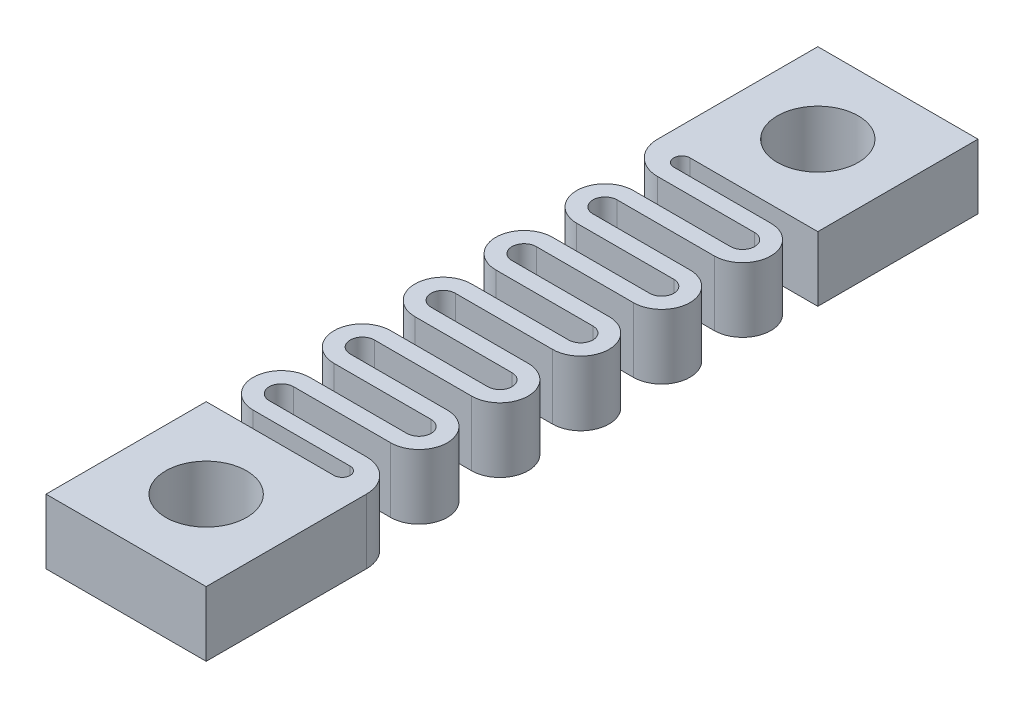
SolidWorks part; units mm, degrees
ref_plane "前视基准面" through (0, 0, 0) normal (0, 0, 1) x (1, 0, 0)
ref_plane "上视基准面" through (0, 0, 0) normal (0, 1, 0) x (1, 0, 0)
ref_plane "右视基准面" through (0, 0, 0) normal (1, 0, 0) x (0, 0, -1)
other "Configuration Table"
sketch "草图1" plane through (0, 0, 0) normal (0, 1, 0) x (1, 0, 0)
  line L1 (-4.95, 4.95) -> (4.95, 4.95)
  line L2 (-4.95, 4.95) -> (-4.95, -4.95)
  line L3 (-4.95, -4.95) -> (4.95, -4.95)
  line L4 (4.95, 4.95) -> (4.95, -4.95)
  line L5 (-4.95, 4.95) -> (4.95, -4.95) construction
  line L6 (-4.95, -4.95) -> (4.95, 4.95) construction
  circle A0 centre (0, 0) radius 2.5
  point P1 (0, 0)
  dimension "D3" = 5
  dimension "D1" = 9.9
  dimension "D2" = 9.9
extrude "凸台-拉伸1" add sketch "草图1" along normal blind 4
sketch "草图2" plane through (0, 0, 0) normal (0, 1, 0) x (1, 0, 0)
  line L0 (-4.95, -4.95) -> (0.3907, -4.95) construction
  line L1 (3.05, -6.95) -> (-2.95, -6.95)
  line L2 (3.05, -9.45) -> (-2.95, -9.45)
  line L3 (3.05, -5.95) -> (-2.95, -5.95)
  line L4 (3.05, -8.45) -> (-2.95, -8.45)
  line L5 (-2.95, -10.95) -> (3.05, -10.95)
  line L6 (-2.95, -11.95) -> (3.05, -11.95)
  line L7 (3.05, -13.45) -> (-2.95, -13.45)
  line L8 (3.05, -14.45) -> (-2.95, -14.45)
  line L9 (-2.95, -15.95) -> (3.05, -15.95)
  line L10 (-2.95, -16.95) -> (3.05, -16.95)
  line L11 (3.05, -18.45) -> (-2.95, -18.45)
  line L12 (3.05, -19.45) -> (-2.95, -19.45)
  line L13 (-2.95, -20.95) -> (3.05, -20.95)
  line L14 (-2.95, -21.95) -> (3.05, -21.95)
  line L15 (3.05, -23.45) -> (-2.95, -23.45)
  line L16 (3.05, -24.45) -> (-2.95, -24.45)
  line L17 (-2.95, -25.95) -> (3.05, -25.95)
  line L18 (-2.95, -26.95) -> (3.05, -26.95)
  line L19 (3.05, -28.45) -> (-2.95, -28.45)
  line L20 (3.05, -29.45) -> (-2.95, -29.45)
  line L21 (-2.95, -30.95) -> (3.05, -30.95)
  line L22 (-2.95, -31.95) -> (3.05, -31.95)
  line L27 (-4.95, -4.95) -> (4.95, -4.95) construction
  line L28 (3.05, -30.95) -> (3.05, -31.95) construction
  line L29 (3.05, -31.95) -> (3.05, -35.0378) construction
  line L30 (3.05, -32.95) -> (6.0171, -32.95) construction
  line L31 (3.05, -32.95) -> (5.05, -32.95)
  line L32 (-2.95, -4.95) -> (-4.95, -4.95)
  line L33 (3.05, -10.95) -> (3.05, -14.45) construction
  arc A0 (-2.95, -6.95) -> (-4.95, -4.95) centre (-2.95, -4.95) cw
  arc A1 (3.05, -6.95) -> (3.05, -8.45) centre (3.05, -7.7) cw
  arc A2 (3.05, -5.95) -> (3.05, -9.45) centre (3.05, -7.7) cw
  arc A3 (-2.95, -5.95) -> (-2.95, -4.95) centre (-2.95, -5.45) cw
  arc A4 (-2.95, -9.45) -> (-2.95, -10.95) centre (-2.95, -10.2) ccw
  arc A5 (-2.95, -8.45) -> (-2.95, -11.95) centre (-2.95, -10.2) ccw
  arc A7 (3.05, -11.95) -> (3.05, -13.45) centre (3.05, -12.7) cw
  arc A8 (-2.95, -13.45) -> (-2.95, -16.95) centre (-2.95, -15.2) ccw
  arc A9 (-2.95, -14.45) -> (-2.95, -15.95) centre (-2.95, -15.2) ccw
  arc A10 (3.05, -15.95) -> (3.05, -19.45) centre (3.05, -17.7) cw
  arc A11 (3.05, -16.95) -> (3.05, -18.45) centre (3.05, -17.7) cw
  arc A12 (-2.95, -18.45) -> (-2.95, -21.95) centre (-2.95, -20.2) ccw
  arc A13 (-2.95, -19.45) -> (-2.95, -20.95) centre (-2.95, -20.2) ccw
  arc A14 (3.05, -20.95) -> (3.05, -24.45) centre (3.05, -22.7) cw
  arc A15 (3.05, -21.95) -> (3.05, -23.45) centre (3.05, -22.7) cw
  arc A16 (-2.95, -23.45) -> (-2.95, -26.95) centre (-2.95, -25.2) ccw
  arc A17 (-2.95, -24.45) -> (-2.95, -25.95) centre (-2.95, -25.2) ccw
  arc A18 (3.05, -25.95) -> (3.05, -29.45) centre (3.05, -27.7) cw
  arc A19 (3.05, -26.95) -> (3.05, -28.45) centre (3.05, -27.7) cw
  arc A20 (-2.95, -28.45) -> (-2.95, -31.95) centre (-2.95, -30.2) ccw
  arc A21 (-2.95, -29.45) -> (-2.95, -30.95) centre (-2.95, -30.2) ccw
  arc A26 (-2.95, -5.95) -> (-3.95, -4.95) centre (-2.95, -4.95) cw construction
  arc A28 (3.05, -30.95) -> (5.05, -32.95) centre (3.05, -32.95) cw
  arc A29 (3.05, -31.95) -> (3.05, -32.95) centre (3.05, -32.45) cw
  arc A30 (3.05, -10.95) -> (3.05, -14.45) centre (3.05, -12.7) cw
  dimension "D4" = 1.5
  dimension "D7" = 0.5
  dimension "D8" = 1
  dimension "D9" = 2
  dimension "D6" = 0.5
  dimension "D10" = 1.5
  dimension "D1" = 6
  dimension "D2" = 6
  dimension "D3" = 1.5
  dimension "D5" = 1
  dimension "D11" = 3.5
extrude "凸台-拉伸2" add sketch "草图2" along normal blind 4
sketch "草图3" plane through (0, 0, 0) normal (0, 1, 0) x (1, 0, 0)
  line L0 (-4.85, -42.85) -> (5.05, -32.95) construction
  line L1 (5.05, -32.95) -> (-4.85, -32.95)
  line L2 (5.05, -32.95) -> (5.05, -42.85)
  line L3 (5.05, -42.85) -> (-4.85, -42.85)
  line L4 (-4.85, -32.95) -> (-4.85, -42.85)
  circle A0 centre (0.1, -37.9) radius 2.5
  dimension "D3" = 5
  dimension "D1" = 9.9
  dimension "D2" = 9.9
extrude "凸台-拉伸3" add sketch "草图3" along normal blind 4
